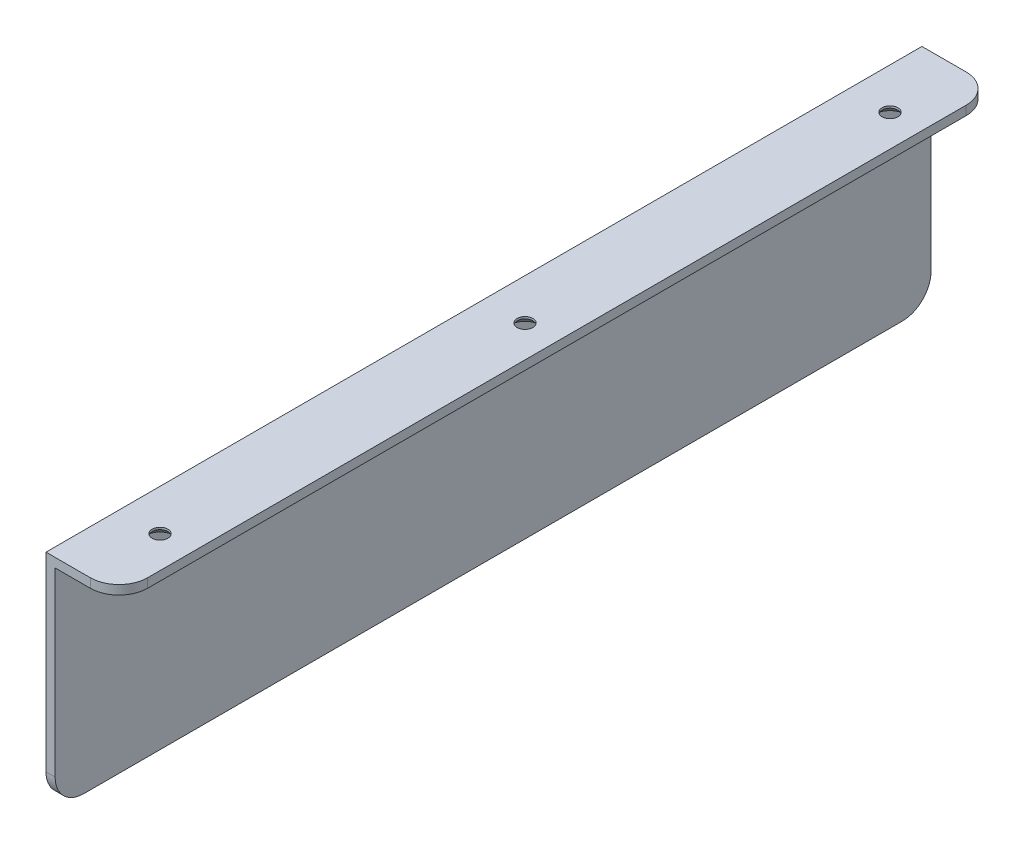
SolidWorks part; units mm, degrees
material "1060 Alloy"
ref_plane "Front Plane" through (0, 0, 0) normal (0, 0, 1) x (1, 0, 0)
ref_plane "Top Plane" through (0, 0, 0) normal (0, 1, 0) x (1, 0, 0)
ref_plane "Right Plane" through (0, 0, 0) normal (1, 0, 0) x (0, 0, -1)
sketch "Sketch1" plane through (0, 0, 0) normal (0, 0, 1) x (1, 0, 0)
  line L0 (0, 0) -> (-25.4, 0)
  line L1 (-25.4, 0) -> (-25.4, -76.2)
  dimension "D1" = 25.4
  dimension "D2" = 76.2
extrude "Extrude-Thin1" add sketch "Sketch1" along normal mid plane 304.8 thin thin type one direction reverse wall 3.175
hole_wizard "CSK for M5 Flat Head Machine Screw1" positions "Sketch2" profile "Sketch3" countersink size "M5" standard "ANSI Metric" end condition through all
sketch "Sketch2" plane through (0, -3.175, 0) normal (0, -1, 0) x (-1, 0, 0)
  line L0 (0, 152.4) -> (22.225, 152.4) construction
  line L1 (0, -152.4) -> (22.225, -152.4) construction
  point P0 (11.1125, -127)
  point P2 (11.1125, 0)
  point P4 (11.1125, 127)
  dimension "D1" = 25.4
  dimension "D2" = 25.4
sketch "Sketch3" plane through (-11.1125, -3.175, 127) normal (1, 0, 0) x (0, 0, -1)
  line L0 (0, 0) -> (0, 3.175)
  line L1 (0, 3.175) -> (2.75, 3.175)
  line L2 (2.75, 3.175) -> (2.75, 2.45)
  line L3 (2.75, 2.45) -> (5.2, 0)
  line L5 (5.2, 0) -> (0, 0)
  line L6 (-2.75, 2.45) -> (-5.2, 0) construction
  line L11 (0, -6.35) -> (0, 107.95) construction
  dimension "Thru Hole Dia." = 5.5
  dimension "Thru Hole Depth" = 3.175
  dimension "Near C'Sink Dia." = 10.4
  dimension "Near C'Sink Angle" = 90
fillet "Fillet1" radius 10 4 edges at (-23.8125, -76.2, -152.4) (0, -1.5875, -152.4) (0, -1.5875, 152.4) (-23.8125, -76.2, 152.4)
